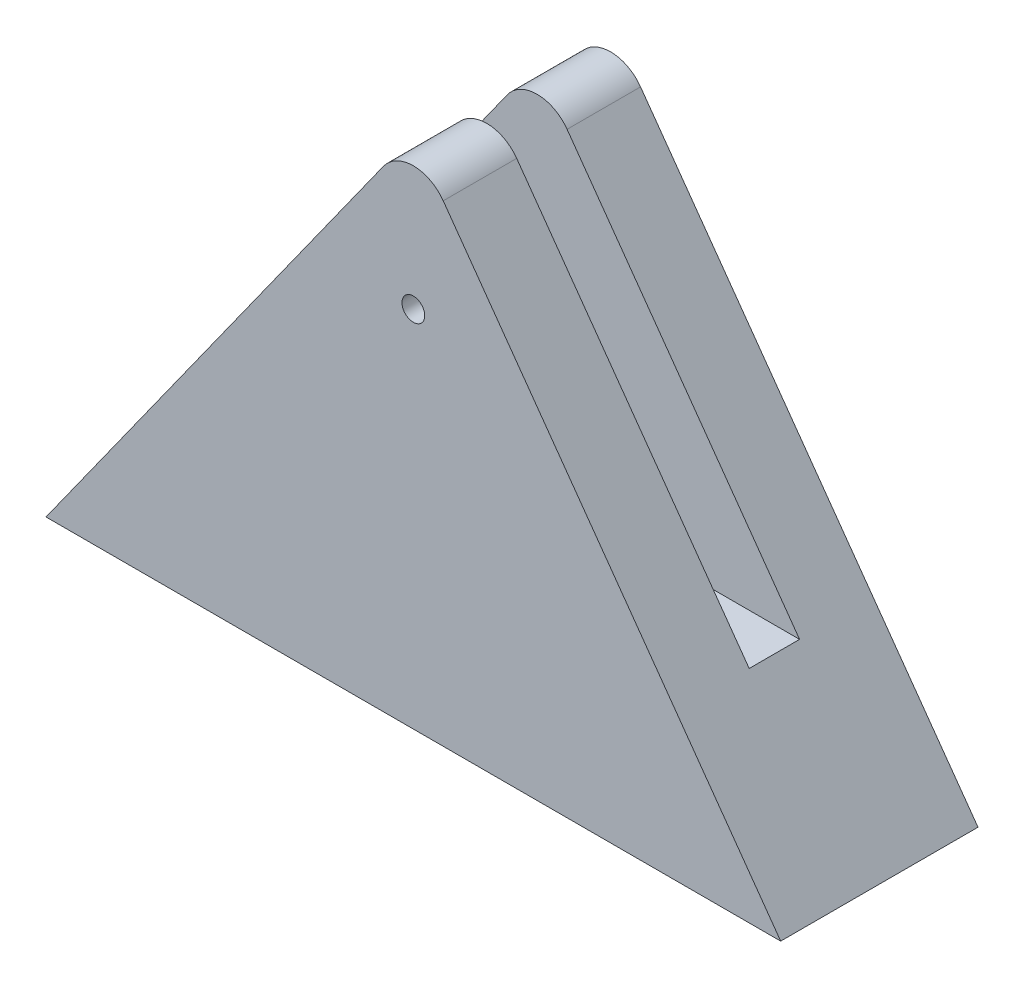
SolidWorks part; units mm, degrees
ref_plane "Front Plane" through (0, 0, 0) normal (0, 0, 1) x (1, 0, 0)
ref_plane "Top Plane" through (0, 0, 0) normal (0, 1, 0) x (1, 0, 0)
ref_plane "Right Plane" through (0, 0, 0) normal (1, 0, 0) x (0, 0, -1)
sketch "Sketch1" plane through (0, 0, 0) normal (0, 0, 1) x (1, 0, 0)
  line L0 (-47.8529, -42.6801) -> (2.1471, 27.3199)
  line L1 (2.1471, 27.3199) -> (52.1471, -42.6801)
  line L2 (52.1471, -42.6801) -> (-47.8529, -42.6801)
  dimension "D1" = 70
  dimension "D2" = 100
extrude "Boss-Extrude1" add sketch "Sketch1" along normal blind 26.858
ref_plane "Plane1" through (52.1471, 0, 0) normal (-1, 0, 0) x (0, 0, 1)
sketch "Sketch2" plane through (52.1471, 0, 0) normal (-1, 0, 0) x (0, 0, 1)
  line L0 (26.858, 27.3199) -> (0, 27.3199) construction
  line L1 (10, 27.3199) -> (16.858, 27.3199)
  line L2 (10, 27.3199) -> (10, -22.6801)
  line L3 (10, -22.6801) -> (16.858, -22.6801)
  line L4 (16.858, 27.3199) -> (16.858, -22.6801)
  line L5 (13.429, 27.3199) -> (13.429, -42.6801) construction
  line L6 (26.858, -42.6801) -> (0, -42.6801) construction
  dimension "D1" = 6.858
  dimension "D2" = 20
extrude "Cut-Extrude1" cut sketch "Sketch2" along normal up to surface (50 mm away)
sketch "Sketch3" plane through (0, 0, 26.858) normal (0, 0, 1) x (1, 0, 0)
  line L0 (2.1471, -42.6801) -> (2.1471, 34.9099) construction
  line L1 (-47.8529, -42.6801) -> (52.1471, -42.6801) construction
  circle A0 centre (2.1471, 6.8199) radius 1.55
  dimension "D1" = 3.1
  dimension "D2" = 49.5
extrude "Cut-Extrude2" cut sketch "Sketch3" against normal up to surface (26.858 mm away) up to face at (2.1471, -19.3468, 0)
fillet "Fillet1" radius 5 2 edges at (2.1471, 27.3199, 5) (2.1471, 27.3199, 21.858)
